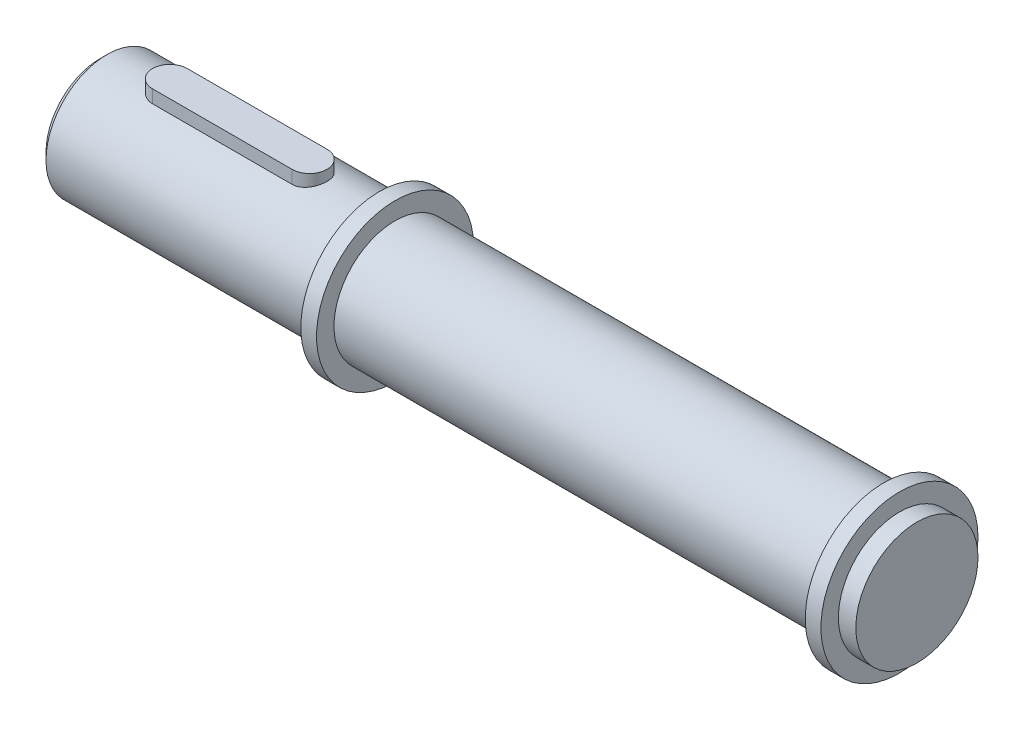
SolidWorks part; units mm, degrees
ref_plane "Front Plane" through (0, 0, 0) normal (0, 0, 1) x (1, 0, 0)
ref_plane "Top Plane" through (0, 0, 0) normal (0, 1, 0) x (1, 0, 0)
ref_plane "Right Plane" through (0, 0, 0) normal (1, 0, 0) x (0, 0, -1)
sketch "Sketch1" plane through (0, 0, 0) normal (0, 0, 1) x (1, 0, 0)
  line L0 (-74.5, 22.5) -> (-74.5, 0)
  line L1 (-74.5, 0) -> (74.5, 0)
  line L2 (74.5, 0) -> (74.5, 22.5)
  line L3 (74.5, 22.5) -> (70, 22.5)
  line L4 (70, 22.5) -> (70, 17.5)
  line L5 (70, 17.5) -> (-70, 17.5)
  line L6 (-70, 17.5) -> (-70, 22.5)
  line L7 (-70, 22.5) -> (-74.5, 22.5)
  line L8 (-74.5, 0) -> (74.5, 0) construction
revolve "Revolve1" add sketch "Sketch1" angle 360 about L8
sketch "Sketch2" plane through (-74.5, 0, 0) normal (-1, 0, 0) x (0, 0, 1)
  circle A0 centre (0, 0) radius 17.5
extrude "Boss-Extrude1" add sketch "Sketch2" along normal blind 80
ref_plane "Plane1" through (0, 20.5, 0) normal (0, 1, 0) x (1, 0, 0)
sketch "Sketch3" plane through (0, 20.5, 0) normal (0, 1, 0) x (1, 0, 0)
  line L0 (-134.5, -5) -> (-94.5, -5)
  line L1 (-94.5, 5) -> (-134.5, 5)
  arc A0 (-94.5, -5) -> (-94.5, 5) centre (-94.5, 0) ccw
  arc A1 (-134.5, 5) -> (-134.5, -5) centre (-134.5, 0) ccw
extrude "Boss-Extrude2" add sketch "Sketch3" against normal up to next
sketch "Sketch4" plane through (74.5, 0, 0) normal (1, 0, 0) x (0, 0, -1)
  circle A0 centre (0, 0) radius 17.5
extrude "Boss-Extrude3" add sketch "Sketch4" along normal blind 5
hole_wizard "Hole1" positions "Sketch6" profile "Sketch5" legacy
sketch "Sketch6" plane through (-154.5, 0, 0) normal (-1, 0, 0) x (0, 0, 1)
  point P0 (0, 0)
sketch "Sketch5" plane through (-154.5, 0, 0) normal (0, 1, 0) x (0, 0, 1)
  line L0 (0, 0) -> (0, 40.4174)
  line L1 (0, 40.4174) -> (5.053, 37.5)
  line L2 (5.053, 37.5) -> (5.053, 9.5)
  line L3 (5.053, 9.5) -> (6.5, 9.5)
  line L4 (6.5, 0) -> (0, 0)
  line L5 (0, -11.3109) -> (0, 121.1557) construction
  line L6 (0, 40.4174) -> (-5.053, 37.5) construction
  line L7 (6.5, 9.5) -> (6.5, 0)
  dimension "Depth" = 37.5
  dimension "Drill Angle" = 120
  dimension "Diameter" = 10.106
  dimension "C-Bore Diameter" = 13
  dimension "C-Bore Depth" = 9.5
chamfer "Chamfer1" distance 2.55 angle 45 1 edges at (-154.5, 0, 6.5)
chamfer "Chamfer2" distance 2 angle 45 1 edges at (-154.5, 0, 17.5)
